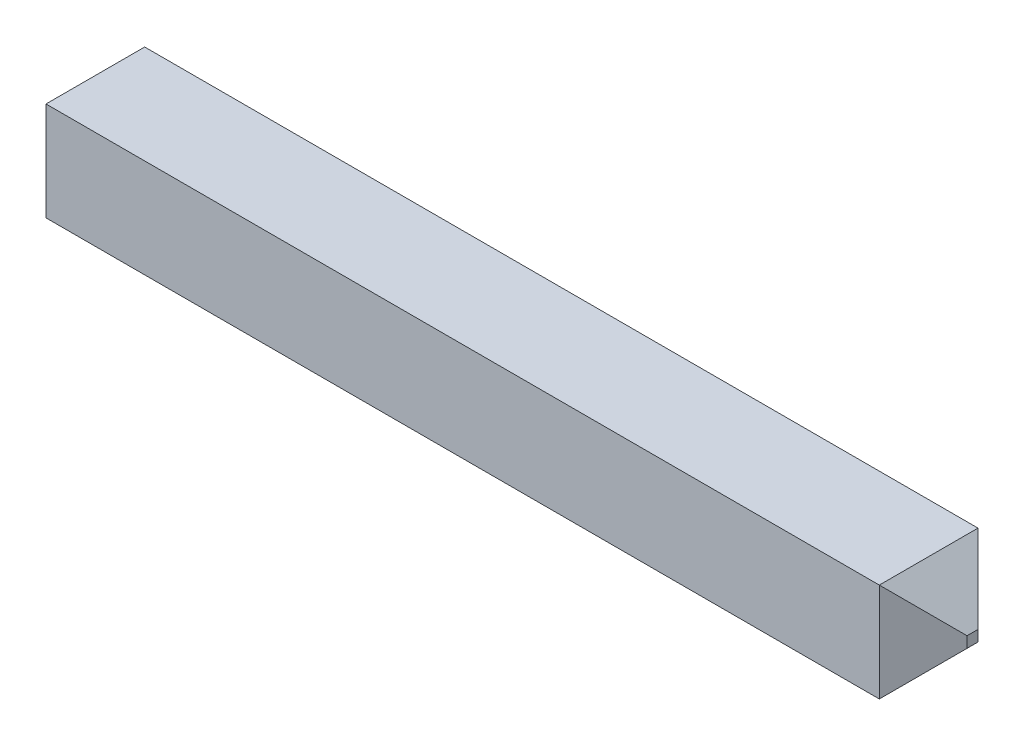
SolidWorks part; units mm, degrees
ref_plane "Alzado" through (0, 0, 0) normal (0, 0, 1) x (1, 0, 0)
ref_plane "Planta" through (0, 0, 0) normal (0, 1, 0) x (1, 0, 0)
ref_plane "Vista lateral" through (0, 0, 0) normal (1, 0, 0) x (0, 0, -1)
ref_plane "Plano4" through (0, 0, -0.225) normal (0, 0, -1) x (-1, 0, 0)
sketch "Croquis1" plane through (0, 0, -0.225) normal (0, 0, -1) x (-1, 0, 0)
  line L0 (0, 0.225) -> (-4, 0.225)
  line L1 (-4, 0.225) -> (-4, -0.225)
  line L2 (-4, -0.225) -> (0, -0.225)
  line L3 (0, -0.225) -> (0, 0.225)
extrude "Saliente-Extruir1" add sketch "Croquis1" against normal blind 0.45
chamfer "Chaflán1" distance 0.2 angle 45 4 edges at (4, 0, -0.225) (4, -0.225, 0) (4, 0.225, 0) (4, 0, 0.225)
